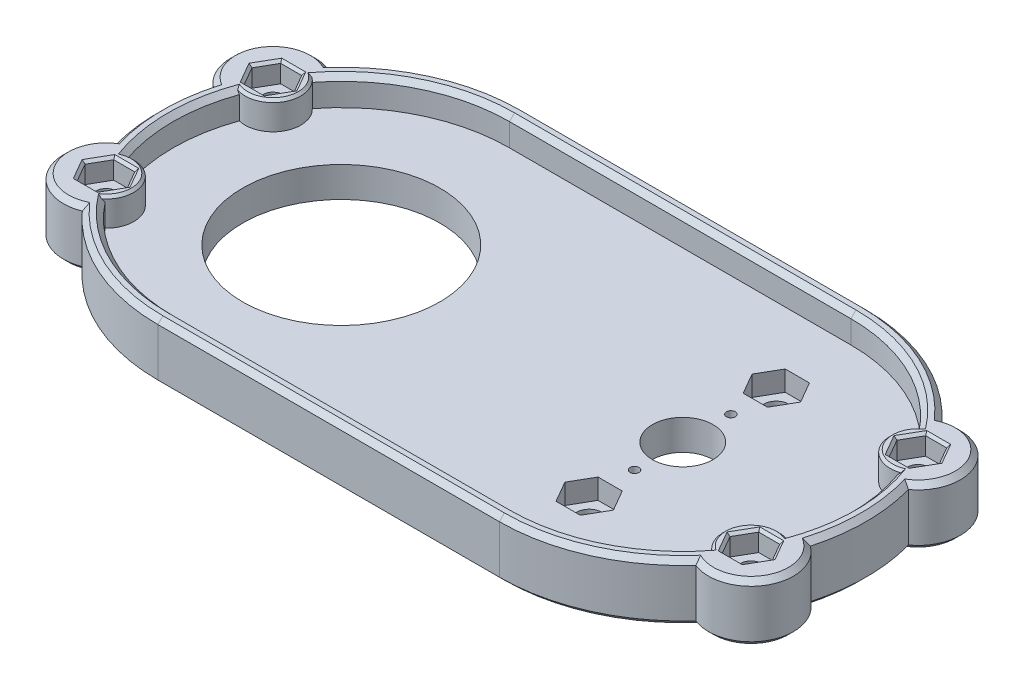
SolidWorks part; units mm, degrees
ref_plane "Front Plane" through (0, 0, 0) normal (0, 0, 1) x (1, 0, 0)
ref_plane "Top Plane" through (0, 0, 0) normal (0, 1, 0) x (1, 0, 0)
ref_plane "Right Plane" through (0, 0, 0) normal (1, 0, 0) x (0, 0, -1)
sketch "Sketch1" plane through (0, 0, 0) normal (0, 1, 0) x (1, 0, 0)
  line L0 (-54.6071, 0) -> (141.8943, 0) construction
  line L1 (67.5, 18.5) -> (67.5, -18.5) construction
  line L2 (-30, 16.5) -> (-30, -16.5) construction
  line L3 (97.5, 16.5) -> (97.5, -16.5) construction
  line L4 (0, 36.25) -> (67.5, 36.25)
  line L5 (0, -36.25) -> (67.5, -36.25)
  line L6 (0, 20.25) -> (67.5, 20.25) construction
  line L7 (0, -20.25) -> (67.5, -20.25) construction
  circle A0 centre (0, 0) radius 19.5
  circle A1 centre (0, 0) radius 25 construction
  arc A6 (0, 36.25) -> (-26.8948, 24.305) centre (0, 0) ccw
  circle A7 centre (67.5, 0) radius 6
  circle A8 centre (67.5, 18.5) radius 2.5
  circle A9 centre (67.5, -18.5) radius 2.5
  circle A10 centre (-30, 16.5) radius 2
  circle A11 centre (-30, -16.5) radius 2
  circle A12 centre (97.5, -16.5) radius 2
  circle A13 centre (97.5, 16.5) radius 2
  arc A14 (-26.8948, 24.305) -> (-34.9287, 9.6979) centre (-30, 16.5) ccw
  arc A15 (-34.9287, -9.6979) -> (-26.8948, -24.305) centre (-30, -16.5) ccw
  arc A16 (102.4287, 9.6979) -> (94.3948, 24.305) centre (97.5, 16.5) ccw
  arc A17 (94.3948, -24.305) -> (102.4287, -9.6979) centre (97.5, -16.5) ccw
  arc A18 (67.5, -36.25) -> (94.3948, -24.305) centre (67.5, 0) ccw
  circle A19 centre (0, 0) radius 20.25 construction
  circle A21 centre (67.5, 0) radius 20.25 construction
  arc A22 (-34.9287, 9.6979) -> (-34.9287, -9.6979) centre (0, 0) ccw
  arc A23 (-26.8948, -24.305) -> (0, -36.25) centre (0, 0) ccw
  arc A24 (94.3948, 24.305) -> (67.5, 36.25) centre (67.5, 0) ccw
  arc A25 (102.4287, -9.6979) -> (102.4287, 9.6979) centre (67.5, 0) ccw
  dimension "D1" = 39
  dimension "D2" = 50
  dimension "D4" = 72.5
  dimension "D5" = 12
  dimension "D7" = 5
  dimension "D10" = 4
  dimension "D11" = 16.8
  dimension "D14" = 72.5
  dimension "D15" = 40.5
  dimension "D6" = 67.5
  dimension "D8" = 37
  dimension "D9" = 33
  dimension "D12" = 30
  dimension "D13" = 30
extrude "Boss-Extrude1" add sketch "Sketch1" along normal blind 6
sketch "Sketch5" plane through (0, 6, 0) normal (0, 1, 0) x (1, 0, 0)
  line L0 (0, 33.25) -> (67.5, 33.25)
  line L7 (0, -33.25) -> (67.5, -33.25)
  line L8 (0, 36.25) -> (67.5, 36.25)
  line L9 (0, -36.25) -> (67.5, -36.25)
  circle A0 centre (-30, 16.5) radius 2
  circle A1 centre (97.5, 16.5) radius 2
  circle A2 centre (97.5, -16.5) radius 2
  circle A3 centre (-30, -16.5) radius 2
  circle A4 centre (-30, 16.5) radius 2 construction
  circle A5 centre (-30, -16.5) radius 2 construction
  circle A6 centre (97.5, 16.5) radius 2 construction
  circle A7 centre (97.5, -16.5) radius 2 construction
  circle A12 centre (0, 0) radius 20.28 construction
  circle A13 centre (67.5, 0) radius 20.28 construction
  arc A14 (0, 33.25) -> (-26.1983, 20.4746) centre (0, 0) ccw
  arc A15 (93.6983, 20.4746) -> (67.5, 33.25) centre (67.5, 0) ccw
  arc A16 (67.5, -33.25) -> (93.6983, -20.4746) centre (67.5, 0) ccw
  arc A17 (0, -36.25) -> (-26.8948, -24.305) centre (0, 0) cw
  arc A18 (0, 36.25) -> (-26.8948, 24.305) centre (0, 0) ccw
  arc A19 (67.5, 36.25) -> (94.3948, 24.305) centre (67.5, 0) cw
  arc A20 (67.5, -36.25) -> (94.3948, -24.305) centre (67.5, 0) ccw
  arc A21 (-34.9287, 9.6979) -> (-34.9287, -9.6979) centre (0, 0) ccw
  arc A22 (-34.9287, 9.6979) -> (-34.9287, -9.6979) centre (0, 0) ccw construction
  arc A23 (102.4287, 9.6979) -> (102.4287, -9.6979) centre (67.5, 0) cw
  arc A24 (-31.3208, 11.161) -> (-26.1983, 20.4746) centre (-30, 16.5) ccw
  arc A26 (98.8208, -11.161) -> (93.6983, -20.4746) centre (97.5, -16.5) ccw
  arc A27 (93.6983, 20.4746) -> (98.8208, 11.161) centre (97.5, 16.5) ccw
  arc A28 (-26.1983, -20.4746) -> (-31.3208, -11.161) centre (-30, -16.5) ccw
  arc A29 (-26.8948, 24.305) -> (-34.9287, 9.6979) centre (-30, 16.5) ccw
  arc A30 (-34.9287, -9.6979) -> (-26.8948, -24.305) centre (-30, -16.5) ccw
  arc A31 (-34.9287, -9.6979) -> (-26.8948, -24.305) centre (-30, -16.5) ccw construction
  arc A32 (94.3948, 24.305) -> (102.4287, 9.6979) centre (97.5, 16.5) cw
  arc A33 (102.4287, -9.6979) -> (94.3948, -24.305) centre (97.5, -16.5) cw
  arc A34 (94.3948, -24.305) -> (102.4287, -9.6979) centre (97.5, -16.5) ccw construction
  arc A35 (-31.3208, 11.161) -> (-31.3208, -11.161) centre (0, 0) ccw
  arc A36 (98.8208, -11.161) -> (98.8208, 11.161) centre (67.5, 0) ccw
  arc A37 (-26.1983, -20.4746) -> (0, -33.25) centre (0, 0) ccw
  dimension "D1" = 40.56
  dimension "D2" = 66.5
  dimension "D4" = 66.5
  dimension "D5" = 11
  dimension "D6" = 11
  dimension "D7" = 11
  dimension "D8" = 11
extrude "Boss-Extrude2" add sketch "Sketch5" along normal blind 5.5
sketch "Sketch6" plane through (0, 11.5, 0) normal (0, 1, 0) x (1, 0, 0)
  line L1 (-25.8431, 16.5) -> (-27.9215, 20.1)
  line L2 (-27.9215, 20.1) -> (-32.0785, 20.1)
  line L3 (-32.0785, 20.1) -> (-34.1569, 16.5)
  line L4 (-34.1569, 16.5) -> (-32.0785, 12.9)
  line L5 (-32.0785, 12.9) -> (-27.9215, 12.9)
  line L6 (-27.9215, 12.9) -> (-25.8431, 16.5)
  line L7 (-34.1569, -16.5) -> (-32.0785, -20.1)
  line L8 (-32.0785, -20.1) -> (-27.9215, -20.1)
  line L9 (-27.9215, -20.1) -> (-25.8431, -16.5)
  line L10 (-25.8431, -16.5) -> (-27.9215, -12.9)
  line L11 (-27.9215, -12.9) -> (-32.0785, -12.9)
  line L12 (-32.0785, -12.9) -> (-34.1569, -16.5)
  line L13 (101.6569, 16.5) -> (99.5785, 20.1)
  line L14 (99.5785, 20.1) -> (95.4215, 20.1)
  line L15 (95.4215, 20.1) -> (93.3431, 16.5)
  line L16 (93.3431, 16.5) -> (95.4215, 12.9)
  line L17 (95.4215, 12.9) -> (99.5785, 12.9)
  line L18 (99.5785, 12.9) -> (101.6569, 16.5)
  line L19 (99.5785, -20.1) -> (101.6569, -16.5)
  line L20 (101.6569, -16.5) -> (99.5785, -12.9)
  line L21 (99.5785, -12.9) -> (95.4215, -12.9)
  line L22 (95.4215, -12.9) -> (93.3431, -16.5)
  line L23 (93.3431, -16.5) -> (95.4215, -20.1)
  line L24 (95.4215, -20.1) -> (99.5785, -20.1)
  circle A0 centre (-30, 16.5) radius 3.6 construction
  circle A1 centre (-30, -16.5) radius 3.6 construction
  circle A2 centre (97.5, 16.5) radius 3.6 construction
  circle A3 centre (97.5, -16.5) radius 3.6 construction
  dimension "D1" = 7.2
  dimension "D2" = 7.2
  dimension "D3" = 7.2
  dimension "D4" = 7.2
extrude "Cut-Extrude2" cut sketch "Sketch6" against normal blind 4
chamfer "Chamfer1" distance 1 angle 45 32 edges at (-37.3602, 0, -20.5481) (-36.25, 0, 0) (-37.3602, 0, 20.5481) (-14.7141, 0, 33.1294) (-14.7141, 0, -33.1294) (33.75, 0, 36.25) (33.75, 0, -36.25) (82.2141, 0, 33.1294) (104.8602, 0, 20.5481) (103.75, 0, 0) (104.8602, 0, -20.5481) (82.2141, 0, -33.1294) (82.0736, 11.5, 29.886) (33.75, 11.5, 33.25) (-14.5736, 11.5, 29.886) (-33.25, 11.5, 0) (-37.3602, 11.5, -20.5481) (-37.3602, 11.5, 20.5481) (-36.25, 11.5, 0) (-14.5736, 11.5, -29.886) (33.75, 11.5, -33.25) (82.0736, 11.5, -29.886) (100.75, 11.5, 0) (-14.7141, 11.5, 33.1294) (-14.7141, 11.5, -33.1294) (33.75, 11.5, 36.25) (33.75, 11.5, -36.25) (82.2141, 11.5, 33.1294) (104.8602, 11.5, 20.5481) (103.75, 11.5, 0) (104.8602, 11.5, -20.5481) (82.2141, 11.5, -33.1294)
chamfer "Chamfer2" distance 0.5 angle 45 28 edges at (-30, 11.5, -12.9) (-33.1177, 11.5, -14.7) (-33.1177, 11.5, -18.3) (-30, 11.5, -20.1) (-26.8823, 11.5, -14.7) (-26.8823, 11.5, -18.3) (-25.1808, 11.5, -13.8494) (-30, 11.5, 20.1) (-33.1177, 11.5, 18.3) (-33.1177, 11.5, 14.7) (-30, 11.5, 12.9) (-26.8823, 11.5, 18.3) (-26.8823, 11.5, 14.7) (-25.1808, 11.5, 13.8494) (100.6177, 11.5, 18.3) (97.5, 11.5, 20.1) (94.3823, 11.5, 18.3) (94.3823, 11.5, 14.7) (97.5, 11.5, 12.9) (100.6177, 11.5, 14.7) (92.6808, 11.5, 13.8494) (92.6808, 11.5, -13.8494) (97.5, 11.5, -12.9) (94.3823, 11.5, -14.7) (94.3823, 11.5, -18.3) (97.5, 11.5, -20.1) (100.6177, 11.5, -14.7) (100.6177, 11.5, -18.3)
sketch "Sketch8" plane through (0, 6, 0) normal (0, 1, 0) x (1, 0, 0)
  circle A0 centre (67.5, 0) radius 9.525 construction
  circle A1 centre (67.5, 9.525) radius 0.875
  circle A2 centre (67.5, -9.525) radius 0.875
  dimension "D1" = 19.05
  dimension "D2" = 1.75
extrude "Cut-Extrude3" cut sketch "Sketch8" against normal through all both and the other way through all
sketch "Sketch9" plane through (0, 6, 0) normal (0, 1, 0) x (1, 0, 0)
  line L1 (72.292, 18.5) -> (69.896, 22.65)
  line L2 (69.896, 22.65) -> (65.104, 22.65)
  line L3 (65.104, 22.65) -> (62.708, 18.5)
  line L4 (62.708, 18.5) -> (65.104, 14.35)
  line L5 (65.104, 14.35) -> (69.896, 14.35)
  line L6 (69.896, 14.35) -> (72.292, 18.5)
  line L7 (72.292, -18.5) -> (69.896, -14.35)
  line L8 (69.896, -14.35) -> (65.104, -14.35)
  line L9 (65.104, -14.35) -> (62.708, -18.5)
  line L10 (62.708, -18.5) -> (65.104, -22.65)
  line L11 (65.104, -22.65) -> (69.896, -22.65)
  line L12 (69.896, -22.65) -> (72.292, -18.5)
  circle A0 centre (67.5, 18.5) radius 4.15 construction
  circle A1 centre (67.5, -18.5) radius 4.15 construction
  dimension "D1" = 8.3
  dimension "D2" = 8.3
extrude "Cut-Extrude4" cut sketch "Sketch9" against normal blind 4
